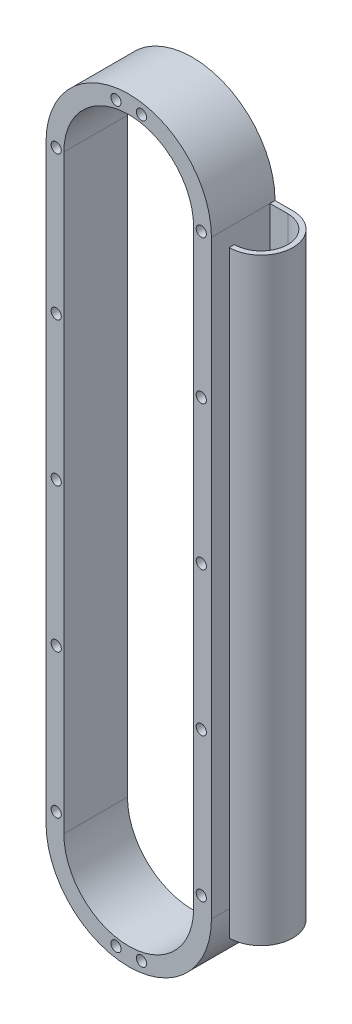
SolidWorks part; units mm, degrees
ref_plane "Front Plane" through (0, 0, 0) normal (0, 0, 1) x (1, 0, 0)
ref_plane "Top Plane" through (0, 0, 0) normal (0, 1, 0) x (1, 0, 0)
ref_plane "Right Plane" through (0, 0, 0) normal (1, 0, 0) x (0, 0, -1)
sketch "Sketch1" plane through (0, 0, 0) normal (0, 0, 1) x (1, 0, 0)
  line L0 (0, -116) -> (0, 116) construction
  line L1 (-32.5, -116) -> (-32.5, 116)
  line L2 (32.5, -116) -> (32.5, 116)
  line L3 (-25.5, -116) -> (-25.5, 116)
  line L4 (25.5, -116) -> (25.5, 116)
  arc A0 (-32.5, -116) -> (32.5, -116) centre (0, -116) ccw
  arc A1 (32.5, 116) -> (-32.5, 116) centre (0, 116) ccw
  arc A2 (25.5, 116) -> (-25.5, 116) centre (0, 116) ccw
  arc A3 (-25.5, -116) -> (25.5, -116) centre (0, -116) ccw
  point P2 (0, 0)
  dimension "D1" = 232
  dimension "D2" = 65
  dimension "D3" = 7
extrude "Boss-Extrude1" add sketch "Sketch1" along normal blind 25
sketch "Sketch2" plane through (0, 0, 25) normal (0, 0, 1) x (1, 0, 0)
  circle A0 centre (-5, 144) radius 2
  circle A1 centre (5, 144) radius 2
  arc A2 (32.5, 116) -> (-32.5, 116) centre (0, 116) ccw construction
  dimension "D1" = 4
  dimension "D2" = 4
  dimension "D3" = 28
  dimension "D4" = 28
  dimension "D5" = 10
  dimension "D6" = 5
extrude "Cut-Extrude1" cut sketch "Sketch2" against normal through all
mirror "Mirror1" about plane through (0, 0, 0) normal (0, 1, 0) of "Cut-Extrude1"
sketch "Sketch4" plane through (0, 0, 25) normal (0, 0, 1) x (1, 0, 0)
  circle A0 centre (28.5, 116) radius 2
  arc A1 (25.5, 116) -> (-25.5, 116) centre (0, 116) ccw construction
  dimension "D1" = 4
  dimension "D2" = 28.5
extrude "Cut-Extrude2" cut sketch "Sketch4" against normal through all
pattern_linear "LPattern1" count 5 spacing 56.5 along (0, -1, 0) of "Cut-Extrude2"
mirror "Mirror2" about plane through (0, 0, 0) normal (1, 0, 0) of "LPattern1", "Cut-Extrude2"
ref_plane "Plane1" through (32.5, 116, 0) normal (0, 1, 0) x (1, 0, 0)
sketch "Sketch5" plane through (32.5, 116, 0) normal (0, 1, 0) x (1, 0, 0)
  line L0 (0, 0) -> (7, 0)
  line L1 (0, -2) -> (7, -2)
  line L2 (0, 0) -> (0, -2)
  line L3 (7, -25) -> (7, -23)
  arc A0 (7, 0) -> (7, -25) centre (7, -12.5) cw
  arc A1 (7, -2) -> (7, -23) centre (7, -12.5) cw
  dimension "D2" = 2
  dimension "D1" = 7
extrude "Boss-Extrude2" add sketch "Sketch5" against normal blind 235
